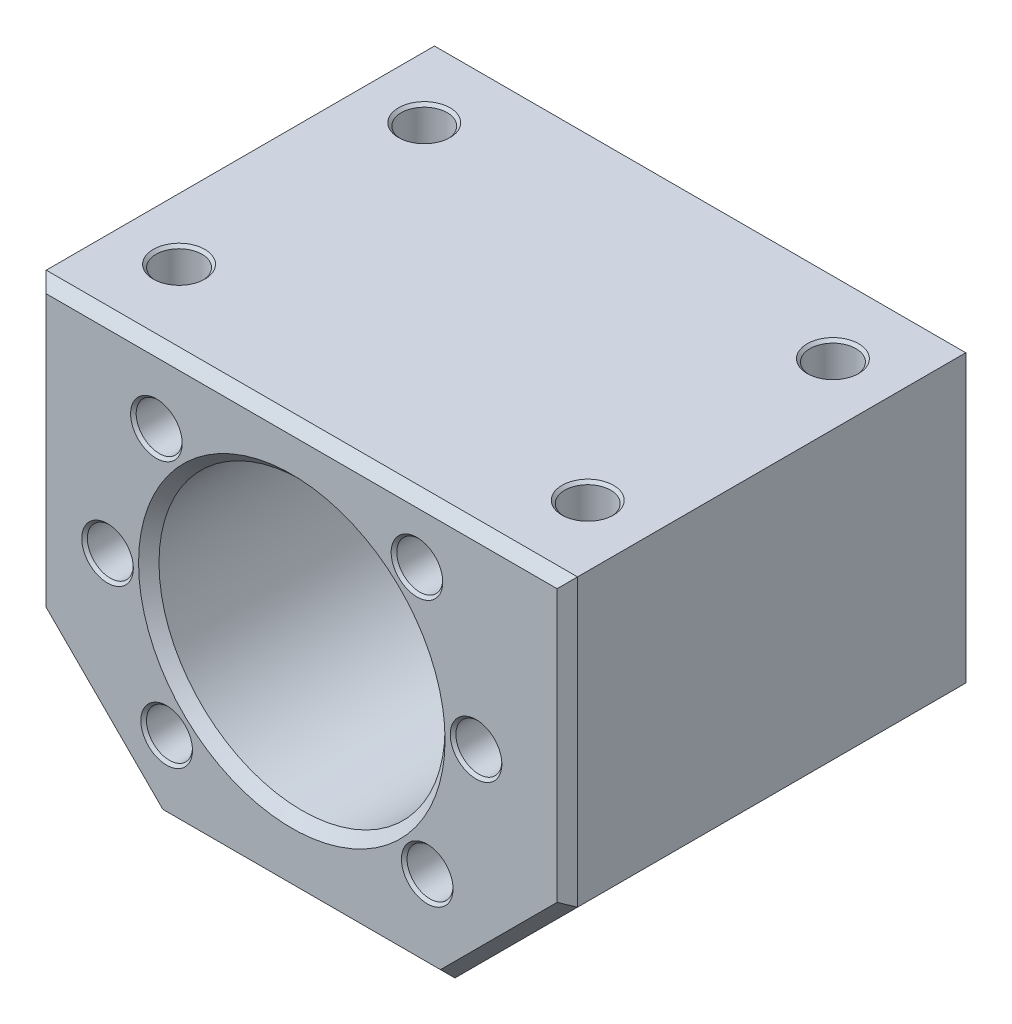
SolidWorks part; units mm, degrees
ref_plane "Front Plane" through (0, 0, 0) normal (0, 0, 1) x (1, 0, 0)
ref_plane "Top Plane" through (0, 0, 0) normal (0, 1, 0) x (1, 0, 0)
ref_plane "Right Plane" through (0, 0, 0) normal (1, 0, 0) x (0, 0, -1)
sketch "Sketch1" plane through (0, 0, 0) normal (0, 0, 1) x (1, 0, 0)
  line L0 (-49.5944, 39.1269) -> (2.4056, 39.1269)
  line L1 (2.4056, 39.1269) -> (2.4056, 11.1269)
  line L2 (2.4056, 11.1269) -> (-9.5944, -0.8731)
  line L3 (-9.5944, -0.8731) -> (-37.5944, -0.8731)
  line L4 (-37.5944, -0.8731) -> (-49.5944, 11.1269)
  line L5 (-49.5944, 11.1269) -> (-49.5944, 39.1269)
  dimension "D1" = 40
  dimension "D2" = 12
  dimension "D3" = 52
  dimension "D4" = 12
  dimension "D5" = 28
  dimension "D6" = 135
extrude "Boss-Extrude1" add sketch "Sketch1" along normal blind 40
sketch "Sketch2" plane through (0, 0, 40) normal (0, 0, 1) x (1, 0, 0)
  circle A0 centre (-24.559, 19.8376) radius 14
  circle A1 centre (-24.559, 19.8376) radius 19
  dimension "D1" = 28
  dimension "D2" = 38
extrude "Cut-Extrude1" cut sketch "Sketch2" against normal blind 40 contours A0
hole_wizard "M5x0.5 Tapped Hole4" positions "Sketch12" profile "Sketch11" tap size "M5x0.5" standard "DIN"
sketch "Sketch12" plane through (0, 39.1269, 0) normal (0, 1, 0) x (1, 0, 0)
  line L0 (-49.5944, -40) -> (-49.5944, 0) construction
  line L1 (2.4056, -40) -> (-49.5944, -40) construction
  line L2 (2.4056, -40) -> (2.4056, 0) construction
  point P0 (-43.5944, -32)
  point P2 (-3.5944, -32)
  point P4 (-3.5944, -8)
  point P6 (-43.5944, -8)
  dimension "D1" = 6
  dimension "D2" = 40
  dimension "D3" = 8
  dimension "D4" = 24
  dimension "D5" = 8
  dimension "D6" = 6
  dimension "D7" = 24
  dimension "D8" = 40
sketch "Sketch11" plane through (-43.5944, 39.1269, 32) normal (1, 0, 0) x (0, 0, 1)
  line L0 (0, 0) -> (0, 12.8519)
  line L1 (0, 12.8519) -> (2.25, 11.5)
  line L2 (2.25, 11.5) -> (2.25, 0.275)
  line L3 (2.25, 0.275) -> (2.525, 0)
  line L5 (2.525, 0) -> (0, 0)
  line L6 (-2.25, 0.275) -> (-2.525, 0) construction
  line L10 (0, 12.8519) -> (-2.25, 11.5) construction
  line L11 (0, -6.35) -> (0, 107.95) construction
  dimension "Tap Drill Dia." = 4.5
  dimension "Tap Drill Depth" = 11.5
  dimension "Near C'Sink Dia." = 5.05
  dimension "Near C'Sink Angle" = 90
  dimension "Drill Angle" = 118
hole_wizard "M5x0.5 Tapped Hole5" positions "Sketch14" profile "Sketch15" tap size "M5x0.5" standard "DIN"
sketch "Sketch14" plane through (0, 0, 40) normal (0, 0, 1) x (1, 0, 0)
  line L0 (2.4056, 39.1269) -> (-49.5944, 39.1269) construction
  line L1 (-49.5944, 39.1269) -> (-49.5944, 11.1269) construction
  line L2 (2.4056, 11.1269) -> (2.4056, 39.1269) construction
  circle A0 centre (-23.5944, 19.1269) radius 19
  point P0 (-42.5944, 19.1269)
  dimension "D3" = 38
  dimension "D1" = 20
  dimension "D2" = 7
  dimension "D4" = 26
  dimension "D5" = 20
sketch "Sketch15" plane through (-42.5944, 19.1269, 40) normal (1, 0, 0) x (0, -1, 0)
  line L0 (0, 0) -> (0, 7.3519)
  line L1 (0, 7.3519) -> (2.25, 6)
  line L2 (2.25, 6) -> (2.25, 0.275)
  line L3 (2.25, 0.275) -> (2.525, 0)
  line L5 (2.525, 0) -> (0, 0)
  line L6 (-2.25, 0.275) -> (-2.525, 0) construction
  line L10 (0, 7.3519) -> (-2.25, 6) construction
  line L11 (0, -6.35) -> (0, 107.95) construction
  dimension "Tap Drill Dia." = 4.5
  dimension "Tap Drill Depth" = 6
  dimension "Near C'Sink Dia." = 5.05
  dimension "Near C'Sink Angle" = 90
  dimension "Drill Angle" = 118
cosmetic thread "Hole Thread8" parameters "D1"=10, "D2"=5
pattern_circular "CirPattern1" count 8 over 360 about axis through (-24.559, 19.8376, 0) along (0, 0, 1) skipping 2, 6 of "M5x0.5 Tapped Hole5"
fillet "Chamfer1" radius 1 12 edges at (-3.5944, 5.1269, 0) (2.4056, 25.1269, 0) (-23.5944, 39.1269, 0) (-49.5944, 25.1269, 0) (-43.5944, 5.1269, 0) (-23.5944, -0.8731, 0) (-3.5944, 5.1269, 40) (2.4056, 25.1269, 40) (-23.5944, -0.8731, 40) (-43.5944, 5.1269, 40) (-23.5944, 39.1269, 40) (-49.5944, 25.1269, 40) profile chamfer
chamfer "Chamfer2" distance 1 angle 45 2 edges at (-10.559, 19.8376, 0) (-10.559, 19.8376, 40)
